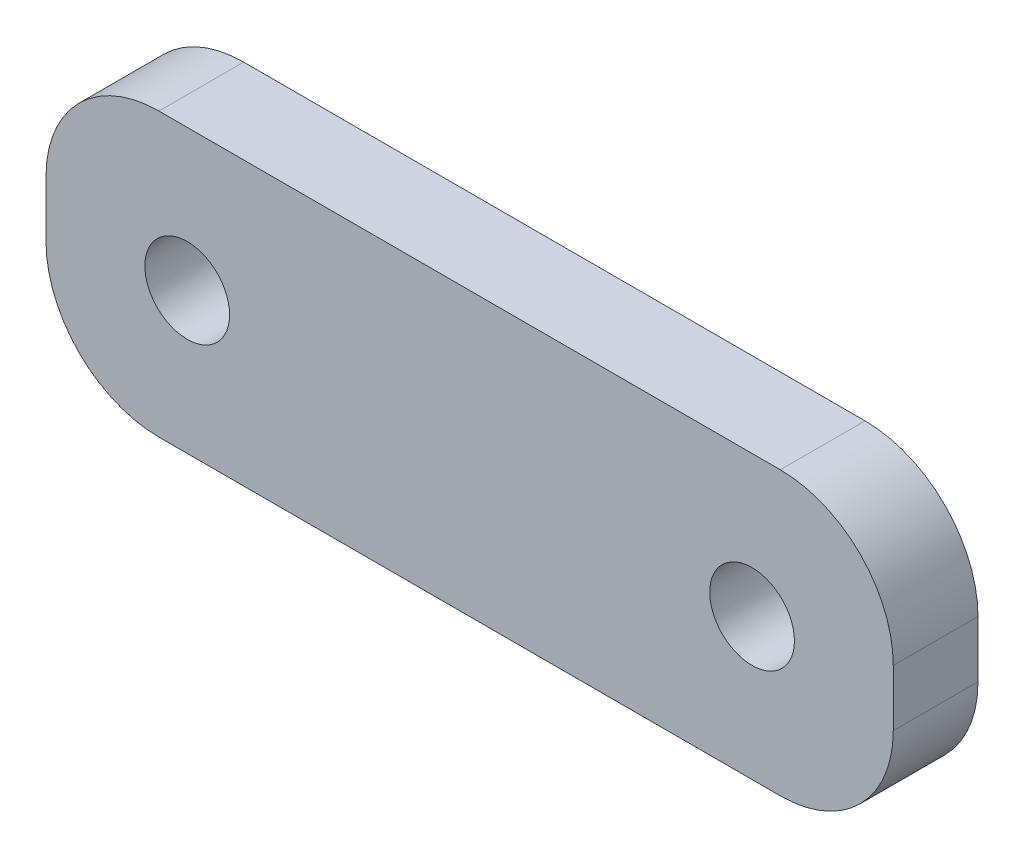
SolidWorks part; units mm, degrees
ref_plane "前视基准面" through (0, 0, 0) normal (0, 0, 1) x (1, 0, 0)
ref_plane "上视基准面" through (0, 0, 0) normal (0, 1, 0) x (1, 0, 0)
ref_plane "右视基准面" through (0, 0, 0) normal (1, 0, 0) x (0, 0, -1)
other "Configuration Table"
sketch "草图1" plane through (0, 0, 0) normal (0, 0, 1) x (1, 0, 0)
  line L1 (-15, 5) -> (15, 5)
  line L2 (-15, 5) -> (-15, -5)
  line L3 (-15, -5) -> (15, -5)
  line L4 (15, 5) -> (15, -5)
  dimension "D1" = 30
  dimension "D2" = 10
  dimension "D3" = 15
  dimension "D4" = 5
extrude "凸台-拉伸1" add sketch "草图1" along normal blind 3
sketch "草图2" plane through (0, 0, 3) normal (0, 0, 1) x (1, 0, 0)
  line L0 (15, 5) -> (-15, 5) construction
  circle A0 centre (10, 0) radius 1.5
  circle A1 centre (-10, 0) radius 1.5
  dimension "D1" = 3
  dimension "D2" = 3
  dimension "D3" = 20
  dimension "D4" = 10
  dimension "D5" = 5
extrude "切除-拉伸1" cut sketch "草图2" against normal blind 3
fillet "圆角1" radius 4 4 edges at (-15, -5, 1.5) (-15, 5, 1.5) (15, -5, 1.5) (15, 5, 1.5)
